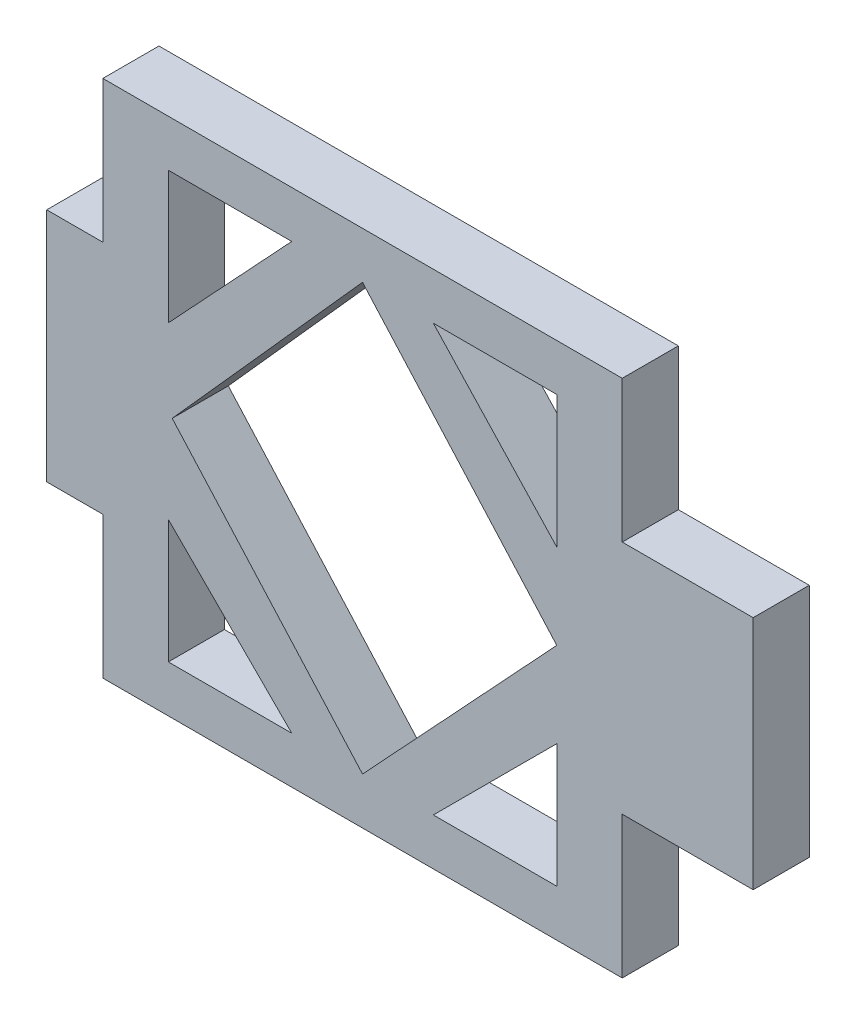
SolidWorks part; units mm, degrees
ref_plane "Alzado" through (0, 0, 0) normal (0, 0, 1) x (1, 0, 0)
ref_plane "Planta" through (0, 0, 0) normal (0, 1, 0) x (1, 0, 0)
ref_plane "Vista lateral" through (0, 0, 0) normal (1, 0, 0) x (0, 0, -1)
sketch "Croquis1" plane through (0, 0, 0) normal (0, 0, 1) x (1, 0, 0)
  line L0 (94.159, 227.8847) -> (470.7948, 227.8847) construction
  line L1 (97.3348, 52.0564) -> (97.3348, 39.4564)
  line L2 (97.3348, 45.7564) -> (141.9124, 45.7564) construction
  line L3 (135.1048, 39.4564) -> (135.1048, 52.0564)
  line L4 (135.1048, 52.0564) -> (128.1048, 52.0564)
  line L5 (128.1048, 52.0564) -> (128.1048, 59.6414)
  line L6 (128.1048, 59.6414) -> (100.3348, 59.6414)
  line L7 (100.3348, 59.6414) -> (100.3348, 52.0564)
  line L8 (100.3348, 52.0564) -> (97.3348, 52.0564)
  line L9 (135.1048, 39.4564) -> (128.1048, 39.4564)
  line L10 (128.1048, 39.4564) -> (128.1048, 31.8714)
  line L11 (128.1048, 31.8714) -> (100.3348, 31.8714)
  line L12 (100.3348, 31.8714) -> (100.3348, 39.4564)
  line L13 (100.3348, 39.4564) -> (97.3348, 39.4564)
  line L20 (110.4348, 57.1414) -> (103.8348, 57.1414)
  line L21 (103.8348, 57.1414) -> (103.8348, 50.0714)
  line L22 (103.8348, 50.0714) -> (110.4348, 57.1414)
  line L23 (103.8348, 40.9714) -> (103.8348, 34.3714)
  line L24 (103.8348, 34.3714) -> (110.4348, 34.3714)
  line L25 (110.4348, 34.3714) -> (103.8348, 40.9714)
  line L26 (118.0048, 34.3714) -> (124.6048, 34.3714)
  line L27 (124.6048, 34.3714) -> (124.6048, 40.9714)
  line L28 (124.6048, 40.9714) -> (118.0048, 34.3714)
  line L29 (124.6048, 50.0764) -> (124.6048, 57.1414)
  line L30 (124.6048, 57.1414) -> (118.0048, 57.1414)
  line L31 (118.0048, 57.1414) -> (124.6048, 50.0764)
  line L32 (110.4348, 57.1414) -> (118.0048, 57.1414) construction
  line L33 (124.6048, 50.0764) -> (124.6048, 40.9714) construction
  line L34 (110.4348, 34.3714) -> (118.0048, 34.3714) construction
  line L35 (114.2198, 57.1414) -> (124.6048, 45.5239)
  line L36 (124.6048, 45.5239) -> (114.2198, 34.3714)
  line L37 (114.2198, 34.3714) -> (104.0427, 45.7564)
  line L38 (104.0427, 45.7564) -> (114.2198, 57.1414)
  point P12 (135.1048, 45.7564)
  dimension "D1" = 6.3
  dimension "D3" = 27.77
  dimension "D4" = 6.3
  dimension "D5" = 7.07
  dimension "D6" = 3
  dimension "D7" = 7
  dimension "D8" = 27.77
  dimension "D9" = 2.5
  dimension "D10" = 2.5
  dimension "D11" = 3.5
  dimension "D12" = 3.5
  dimension "D13" = 3.5
  dimension "D14" = 6.6
  dimension "D15" = 6.6
  dimension "D16" = 6.6
  dimension "D17" = 6.6
  dimension "D18" = 6.6
  dimension "D19" = 6.6
  dimension "D20" = 7.065
  dimension "D21" = 6.3
extrude "Saliente-Extruir1" add sketch "Croquis1" along normal blind 3
